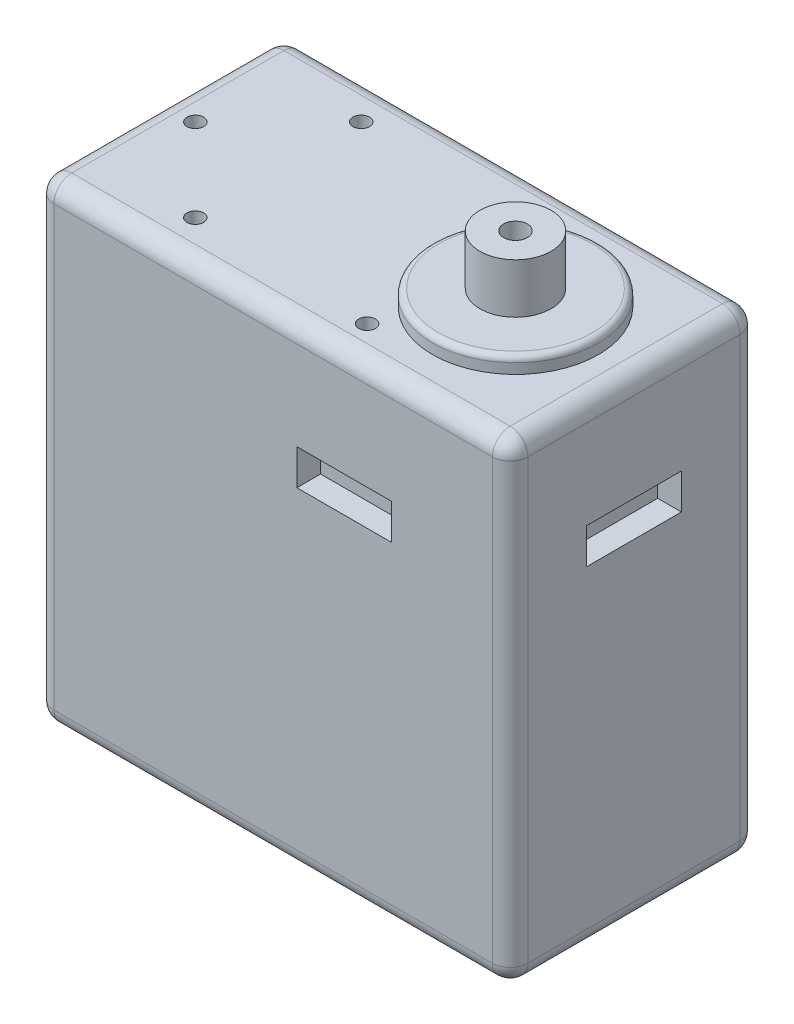
SolidWorks part; units mm, degrees
ref_plane "前视基准面" through (0, 0, 0) normal (0, 0, 1) x (1, 0, 0)
ref_plane "上视基准面" through (0, 0, 0) normal (0, 1, 0) x (1, 0, 0)
ref_plane "右视基准面" through (0, 0, 0) normal (1, 0, 0) x (0, 0, -1)
ref_plane "基准面1" through (0, 0, -10.45) normal (0, 0, -1) x (-1, 0, 0)
sketch "草图1" plane through (0, 0, -10.45) normal (0, 0, -1) x (-1, 0, 0)
  line L0 (30, 20) -> (-10, 20)
  line L1 (-10, 20) -> (-10, -20)
  line L2 (-10, -20) -> (30, -20)
  line L3 (30, -20) -> (30, 20)
extrude "凸台-拉伸1" add sketch "草图1" against normal blind 20.9
sketch "草图2" plane through (0, 0, -10.45) normal (0, 0, -1) x (-1, 0, 0)
  line L0 (0, 8) -> (8, 8)
  line L1 (8, 8) -> (8, 11)
  line L2 (8, 11) -> (0, 11)
  line L3 (0, 11) -> (0, 8)
extrude "切除-拉伸1" cut sketch "草图2" against normal blind 2
sketch "草图3" plane through (0, 0, 10.45) normal (0, 0, 1) x (1, 0, 0)
  line L0 (-8, 8) -> (0, 8)
  line L1 (0, 8) -> (0, 11)
  line L2 (0, 11) -> (-8, 11)
  line L3 (-8, 11) -> (-8, 8)
extrude "切除-拉伸2" cut sketch "草图3" against normal blind 2
sketch "草图4" plane through (10, 0, 0) normal (1, 0, 0) x (0, 0, -1)
  line L0 (-4, 8) -> (4, 8)
  line L1 (4, 8) -> (4, 11)
  line L2 (4, 11) -> (-4, 11)
  line L3 (-4, 11) -> (-4, 8)
extrude "切除-拉伸3" cut sketch "草图4" against normal blind 2
sketch "草图5" plane through (0, 0, 0) normal (0, 0, 1) x (1, 0, 0)
  line L0 (3, 25.55) -> (0, 25.55)
  line L1 (0, 25.55) -> (0, 20)
  line L2 (0, 20) -> (7, 20)
  line L3 (7, 20) -> (7, 21.35)
  line L4 (7, 21.35) -> (3, 21.35)
  line L5 (3, 21.35) -> (3, 25.55)
  line L6 (0, 25.55) -> (0, 20) construction
revolve "旋转1" add sketch "草图5" angle 360 about L6
sketch "草图6" plane through (0, 0, 0) normal (0, 0, 1) x (1, 0, 0)
  line L0 (7, -20) -> (0, -20)
  line L1 (0, -20) -> (0, -25.55)
  line L2 (0, -25.55) -> (3, -25.55)
  line L3 (3, -25.55) -> (3, -21.35)
  line L4 (3, -21.35) -> (7, -21.35)
  line L5 (7, -21.35) -> (7, -20)
  line L6 (0, -20) -> (0, -25.55) construction
revolve "旋转2" add sketch "草图6" angle 360 about L6
hole_wizard "孔1" positions "草图8" profile "草图7" legacy
sketch "草图8" plane through (0, 25.55, 0) normal (0, 1, 0) x (1, 0, 0)
  point P0 (0, 0)
sketch "草图7" plane through (0, 25.55, 0) normal (1, 0, 0) x (0, 0, 1)
  line L0 (0, 0) -> (0, 5.55)
  line L1 (0, 5.55) -> (1, 5.55)
  line L2 (1, 5.55) -> (1, 0)
  line L3 (1, 0) -> (0, 0)
  line L4 (0, 110) -> (0, -10) construction
  dimension "直径" = 2
  dimension "深度" = 5.55
hole_wizard "孔2" positions "草图10" profile "草图9" legacy
sketch "草图10" plane through (0, 20, 0) normal (0, 1, 0) x (1, 0, 0)
  point P0 (-5.02, 7.5)
  point P1 (-5.02, -7.5)
  point P2 (-20.02, 7)
  point P3 (-20.02, -7)
  point P4 (-27.02, 0)
sketch "草图9" plane through (-5.02, 20, -7.5) normal (1, 0, 0) x (0, 0, 1)
  line L0 (0, 0) -> (0, 10)
  line L1 (0, 10) -> (0.7, 10)
  line L2 (0.7, 10) -> (0.7, 0)
  line L3 (0.7, 0) -> (0, 0)
  line L4 (0, 110) -> (0, -10) construction
  dimension "直径" = 1.4
  dimension "深度" = 10
hole_wizard "孔3" positions "草图12" profile "草图11" legacy
sketch "草图12" plane through (0, -25.55, 0) normal (0, -1, 0) x (-1, 0, 0)
  point P0 (0, 0)
sketch "草图11" plane through (0, -25.55, 0) normal (1, 0, 0) x (0, 0, -1)
  line L0 (0, 0) -> (0, 5.55)
  line L1 (0, 5.55) -> (1, 5.55)
  line L2 (1, 5.55) -> (1, 0)
  line L3 (1, 0) -> (0, 0)
  line L4 (0, 110) -> (0, -10) construction
  dimension "直径" = 2
  dimension "深度" = 5.55
hole_wizard "孔4" positions "草图14" profile "草图13" legacy
sketch "草图14" plane through (0, -20, 0) normal (0, -1, 0) x (-1, 0, 0)
  point P0 (27.5, 7.1709)
  point P1 (27.5, -7.1709)
  point P2 (12.5, -7.1709)
  point P3 (-7.5, -7.1709)
  point P4 (-7.5, 7.1709)
  point P5 (12.5, 7.1709)
sketch "草图13" plane through (-27.5, -20, -7.1709) normal (1, 0, 0) x (0, 0, -1)
  line L0 (0, 0) -> (0, 10)
  line L1 (0, 10) -> (0.9, 10)
  line L2 (0.9, 10) -> (0.9, 0)
  line L3 (0.9, 0) -> (0, 0)
  line L4 (0, 110) -> (0, -10) construction
  dimension "直径" = 1.8
  dimension "深度" = 10
fillet "圆角1" radius 0.5 2 edges at (0, -21.35, -7) (0, 21.35, -7)
fillet "圆角2" radius 1.5 12 edges at (-30, 20, 0) (-10, 20, 10.45) (-10, 20, -10.45) (10, 20, 0) (-30, 0, 10.45) (-30, -20, 0) (-30, 0, -10.45) (10, 0, 10.45) (10, 0, -10.45) (10, -20, 0) (-10, -20, 10.45) (-10, -20, -10.45)
